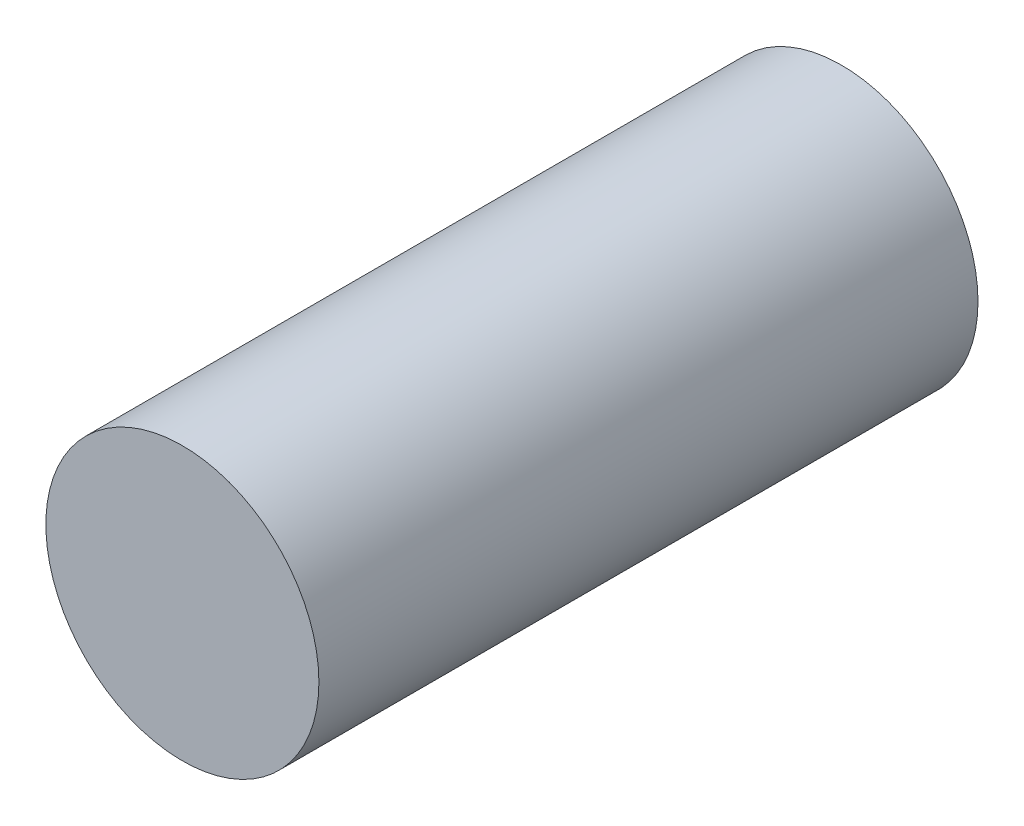
SolidWorks part; units mm, degrees
ref_plane "Front Plane" through (0, 0, 0) normal (0, 0, 1) x (1, 0, 0)
ref_plane "Top Plane" through (0, 0, 0) normal (0, 1, 0) x (1, 0, 0)
ref_plane "Right Plane" through (0, 0, 0) normal (1, 0, 0) x (0, 0, -1)
sketch "Sketch1" plane through (0, 0, 0) normal (0, 0, 1) x (1, 0, 0)
  circle A0 centre (0, 0) radius 1.45
  point P5 (7.6444, 0)
  dimension "D1" = 2.9
extrude "Boss-Extrude1" add sketch "Sketch1" along normal blind 7
